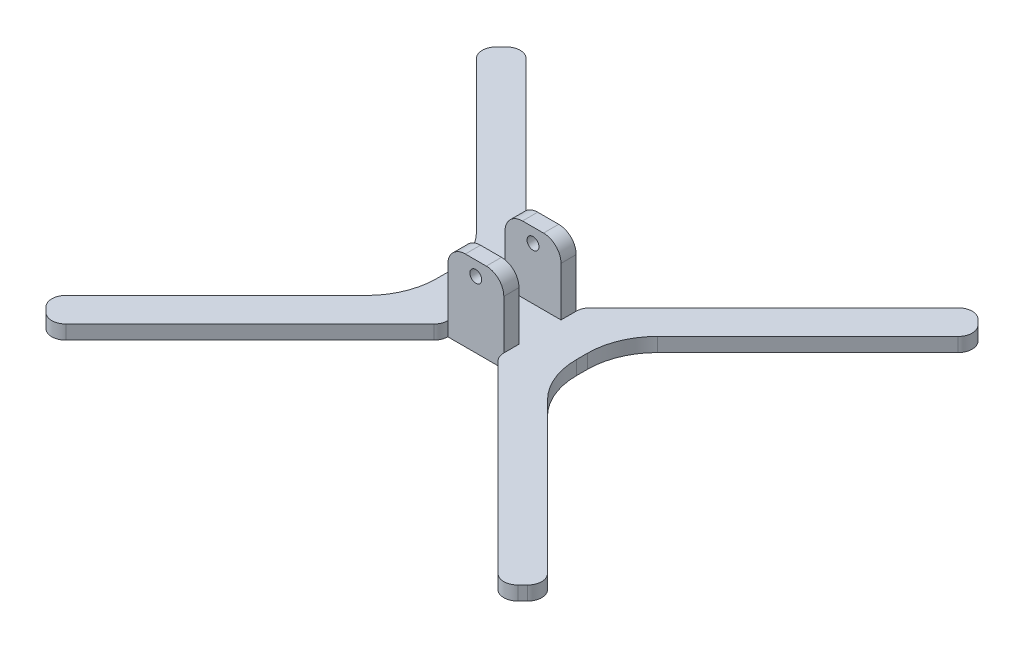
SolidWorks part; units mm, degrees
ref_plane "Front Plane" through (0, 0, 0) normal (0, 0, 1) x (1, 0, 0)
ref_plane "Top Plane" through (0, 0, 0) normal (0, 1, 0) x (1, 0, 0)
ref_plane "Right Plane" through (0, 0, 0) normal (1, 0, 0) x (0, 0, -1)
sketch "Sketch2" plane through (0, 0, 0) normal (0, 1, 0) x (1, 0, 0)
  line L1 (4, 6) -> (32.2843, 34.2843)
  line L2 (10, 4.9289) -> (35.8198, 30.7487)
  line L3 (32.2843, 34.2843) -> (35.8198, 30.7487)
  line L4 (0, -55) -> (0, 55) construction
  line L6 (-32.2843, 34.2843) -> (-35.8198, 30.7487)
  line L8 (-10, 4.9289) -> (-35.8198, 30.7487)
  line L9 (-4, 6) -> (-32.2843, 34.2843)
  line L10 (-55, 0) -> (55, 0) construction
  line L11 (32.2843, -34.2843) -> (35.8198, -30.7487)
  line L12 (10, -4.9289) -> (35.8198, -30.7487)
  line L13 (4, -6) -> (32.2843, -34.2843)
  line L16 (-10, -4.9289) -> (-35.8198, -30.7487)
  line L17 (-32.2843, -34.2843) -> (-35.8198, -30.7487)
  line L18 (-4, -6) -> (-32.2843, -34.2843)
  line L21 (-10, 4.9289) -> (-10, -4.9289)
  line L22 (10, 4.9289) -> (10, -4.9289)
  line L23 (-4, 6) -> (-4, 3)
  line L24 (-4, 3) -> (4, 3)
  line L25 (4, 6) -> (4, 3)
  line L26 (-4, -6) -> (-4, -3)
  line L27 (-4, -3) -> (4, -3)
  line L28 (4, -3) -> (4, -6)
  point P0 (0, 3)
  point P8 (-10, 0)
  point P18 (10, 0)
  point P25 (0, -3)
  dimension "D1" = 40
  dimension "D2" = 5
  dimension "D3" = 8
  dimension "D4" = 3
  dimension "D5" = 6
  dimension "D6" = 90
  dimension "D7" = 45
  dimension "D8" = 3
  dimension "D9" = 6
  dimension "D10" = 6
  dimension "D11" = 90
extrude "Boss-Extrude2" add sketch "Sketch2" along normal blind 2
fillet "Fillet1" radius 2 12 edges at (4, 1, -6) (4, 1, 6) (-4, 1, 6) (-4, 1, -6) (35.8198, 1, -30.7487) (32.2843, 1, -34.2843) (35.8198, 1, 30.7487) (32.2843, 1, 34.2843) (-32.2843, 1, 34.2843) (-35.8198, 1, 30.7487) (-32.2843, 1, -34.2843) (-35.8198, 1, -30.7487)
fillet "Fillet2" radius 10 4 edges at (-10, 1, 4.9289) (-10, 1, -4.9289) (10, 1, -4.9289) (10, 1, 4.9289)
scale "Echelle1" scale about centroid uniform scaling yes scale factor 2
sketch "Esquisse1" plane through (0, -1, 0) normal (0, -1, 0) x (1, 0, 0)
  line L0 (55, 0) -> (-55, 0) construction
  line L1 (-8, -6) -> (8, -6)
  line L2 (-8, -6) -> (-8, -10.3431)
  line L3 (-8, -10.3431) -> (8, -10.3431)
  line L4 (8, -6) -> (8, -10.3431)
  line L5 (8, 6) -> (8, 10.3431)
  line L6 (-8, 6) -> (8, 6)
  line L7 (-8, 6) -> (-8, 10.3431)
  line L8 (-8, 10.3431) -> (8, 10.3431)
extrude "Boss.-Extru.1" add sketch "Esquisse1" against normal offset from surface (23 mm away) 19 up to face at (0, 3, 0) offset beyond the face yes
sketch "Esquisse2" plane through (0, 0, -10.3431) normal (0, 0, -1) x (-1, 0, 0)
  line L0 (0, -3.175) -> (0, 49996.825) construction
  line L1 (8, -1) -> (-8, -1) construction
  circle A0 centre (0, 17.9559) radius 1.7
  point P6 (0, -1)
  dimension "D1" = 3.4
extrude "Enlèv. mat.-Extru.1" cut sketch "Esquisse2" against normal up to surface (20.6863 mm away) up to face at (0, 8, 10.3431)
fillet "Congé1" radius 5 4 edges at (8, 22, -8.1716) (-8, 22, -8.1716) (-8, 22, 8.1716) (8, 22, 8.1716)
equation "\"ScrewSize\"= 3.1mm"
